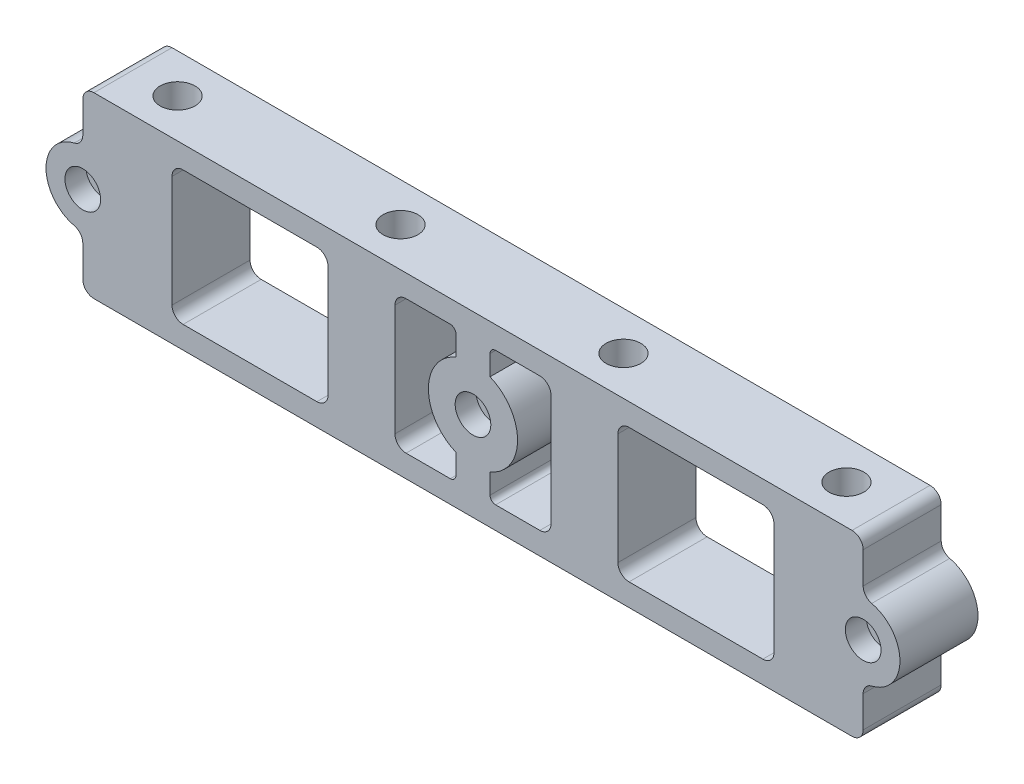
SolidWorks part; units mm, degrees
material "6061-T6 (SS)"
ref_plane "X-Y Datum" through (0, 0, 0) normal (0, 0, 1) x (1, 0, 0)
ref_plane "X-Z Datum" through (0, 0, 0) normal (0, 1, 0) x (1, 0, 0)
ref_plane "Y-Z Datum" through (0, 0, 0) normal (1, 0, 0) x (0, 0, -1)
other "Graphic1"
other "Graphic (Closed) -1"
other "Graphic2"
other "Graphic (Closed) -2"
other "Graphic3"
other "Graphic (Closed) -3"
sketch "Sketch1" plane through (0, 0, 0) normal (0, 0, 1) x (1, 0, 0)
  line L1 (8.7312, 20.32) -> (-186.5312, 20.32)
  line L5 (-8.7312, 0) -> (0, 0) construction
  line L7 (-186.5312, -20.32) -> (-186.5312, 20.32)
  line L8 (-8.7312, 0) -> (-16.6687, 0) construction
  line L9 (-8.7312, 0) -> (-8.7312, 20.32) construction
  line L10 (-8.7312, 20.32) -> (-16.6688, 20.32) construction
  line L11 (-16.6687, 0) -> (-16.6688, 20.32) construction
  line L12 (-67.4688, 0) -> (-59.5313, 0) construction
  line L13 (-67.4688, 0) -> (-67.4688, 20.32) construction
  line L14 (-67.4688, 20.32) -> (-59.5312, 20.32) construction
  line L15 (-59.5313, 0) -> (-59.5312, 20.32) construction
  line L17 (-186.5312, -20.32) -> (8.7312, -20.32)
  line L19 (8.7312, -20.32) -> (8.7312, 20.32)
  line L20 (-110.3313, 20.32) -> (-118.2687, 20.32) construction
  line L21 (-110.3313, 20.32) -> (-110.3313, 0) construction
  line L22 (-110.3313, 0) -> (-118.2687, 0) construction
  line L23 (-118.2687, 20.32) -> (-118.2687, 0) construction
  line L24 (-161.1312, 20.32) -> (-169.0687, 20.32) construction
  line L25 (-161.1312, 20.32) -> (-161.1313, 0) construction
  line L26 (-161.1313, 0) -> (-169.0688, 0) construction
  line L27 (-169.0687, 20.32) -> (-169.0688, 0) construction
  line L28 (0, 0) -> (8.7312, 0) construction
  line L29 (-177.8, 0) -> (-186.5312, 0) construction
  circle A0 centre (0, 0) radius 2.4892
  circle A4 centre (-177.8, 0) radius 2.4892
  circle A6 centre (-88.9, 0) radius 2.4892
  point P1 (-186.5312, 0)
  point P22 (-12.7, 0)
  point P23 (-63.5, 0)
  point P31 (-114.3, 0)
  point P32 (-165.1, 0)
  point P38 (-88.9, -20.32)
  dimension "D2" = 4.9784
  dimension "D3" = 12.7
  dimension "D1" = 50.8
  dimension "D4" = 12.7
  dimension "D6" = 7.9375
  dimension "D7" = 7.9375
  dimension "D8" = 40.64
  dimension "D11" = 50.8
  dimension "D12" = 50.8
extrude "Boss-Extrude1" add sketch "Sketch1" against normal blind 17.78
ref_plane "Plane1" through (0, 0, 0) normal (0, -1, 0) x (-1, 0, 0)
sketch "Sketch2" plane through (0, 20.32, 0) normal (0, 1, 0) x (1, 0, 0)
  line L0 (-186.5312, 0) -> (8.7313, 0) construction
  line L4 (0, 0) -> (0, 17.78) construction
  line L5 (8.7313, 17.78) -> (-186.5312, 17.78) construction
  circle A0 centre (-12.7, 8.89) radius 3.9688
  circle A2 centre (-63.5, 8.89) radius 3.9688
  circle A3 centre (-114.3, 8.89) radius 3.9687
  circle A4 centre (-165.1, 8.89) radius 3.9688
  dimension "D2" = 7.9375
  dimension "D1" = 4
  dimension "D3" = 8.89
  dimension "D4" = 12.7
  dimension "D5" = 50.8
extrude "Cut-Extrude1" cut sketch "Sketch2" against normal up to surface (40.64 mm away) up to face at (-88.9, -20.32, -8.89)
sketch "Sketch3" plane through (0, 0, 0) normal (0, 0, 1) x (1, 0, 0)
  circle A0 centre (0, 0) radius 4.064
  circle A1 centre (-88.9, 0) radius 4.064
  circle A2 centre (-177.8, 0) radius 4.064
  circle A3 centre (-177.8, 0) radius 2.4892 construction
  dimension "D1" = 8.128
extrude "Cut-Extrude2" cut sketch "Sketch3" against normal blind 4.7752
ref_point "Point1"
ref_point "Point2"
ref_point "Point3"
ref_point "Point4"
sketch "Sketch5" plane through (0, 0, 0) normal (0, 0, 1) x (1, 0, 0)
  line L0 (0, -20.32) -> (8.7312, -20.32)
  line L1 (0, -10.6225) -> (0, -20.32)
  line L2 (-186.5312, -20.32) -> (8.7312, -20.32) construction
  line L3 (0, 10.6225) -> (0, 20.32)
  line L4 (8.7312, 20.32) -> (-186.5312, 20.32) construction
  line L5 (8.7312, -20.32) -> (8.7312, 20.32)
  line L6 (8.7312, 20.32) -> (0, 20.32)
  line L7 (-88.9, -20.32) -> (-88.9, 20.32) construction
  line L8 (0, 0) -> (-20.32, 0) construction
  line L9 (-22.86, -15.24) -> (-53.34, -15.24)
  line L10 (-20.32, -12.7) -> (-20.32, 12.7)
  line L11 (-22.86, 15.24) -> (-53.34, 15.24)
  line L12 (-55.88, -12.7) -> (-55.88, 12.7)
  line L13 (-85.0119, -9.3866) -> (-85.0119, -13.97)
  line L14 (-83.7419, -15.24) -> (-73.66, -15.24)
  line L15 (-71.12, -12.7) -> (-71.12, 12.7)
  line L16 (-73.66, 15.24) -> (-83.7419, 15.24)
  line L17 (-85.0119, 13.97) -> (-85.0119, 9.3866)
  line L18 (-88.9, 0) -> (-85.0119, -9.3866) construction
  line L19 (-88.9, 0) -> (-85.0119, 9.3866) construction
  line L20 (-104.14, 15.24) -> (-94.0581, 15.24)
  line L21 (-106.68, -12.7) -> (-106.68, 12.7)
  line L22 (-94.0581, -15.24) -> (-104.14, -15.24)
  line L23 (-92.7881, -9.3866) -> (-92.7881, -13.97)
  line L24 (-92.7881, 13.97) -> (-92.7881, 9.3866)
  line L25 (-154.94, 15.24) -> (-124.46, 15.24)
  line L26 (-121.92, -12.7) -> (-121.92, 12.7)
  line L27 (-154.94, -15.24) -> (-124.46, -15.24)
  line L28 (-157.48, -12.7) -> (-157.48, 12.7)
  line L29 (-186.5312, -20.32) -> (-186.5312, 20.32)
  line L30 (-177.8, -20.32) -> (-186.5312, -20.32)
  line L31 (-177.8, -10.6225) -> (-177.8, -20.32)
  line L32 (-177.8, 10.6225) -> (-177.8, 20.32)
  line L33 (-186.5312, 20.32) -> (-177.8, 20.32)
  arc A0 (1.9493, 8.1522) -> (1.9493, -8.1522) centre (0, 0) cw
  arc A1 (-85.0119, -9.3866) -> (-85.0119, 9.3866) centre (-88.9, 0) ccw
  arc A2 (0, -10.6225) -> (1.9493, -8.1522) centre (2.54, -10.6225) cw
  arc A3 (-22.86, 15.24) -> (-20.32, 12.7) centre (-22.86, 12.7) cw
  arc A4 (-55.88, 12.7) -> (-53.34, 15.24) centre (-53.34, 12.7) cw
  arc A5 (-55.88, -12.7) -> (-53.34, -15.24) centre (-53.34, -12.7) ccw
  arc A6 (0, 10.6225) -> (1.9493, 8.1522) centre (2.54, 10.6225) ccw
  arc A7 (-22.86, -15.24) -> (-20.32, -12.7) centre (-22.86, -12.7) ccw
  arc A8 (-92.7881, -9.3866) -> (-92.7881, 9.3866) centre (-88.9, 0) cw
  arc A9 (-121.92, 12.7) -> (-124.46, 15.24) centre (-124.46, 12.7) ccw
  arc A10 (-121.92, -12.7) -> (-124.46, -15.24) centre (-124.46, -12.7) cw
  arc A11 (-154.94, 15.24) -> (-157.48, 12.7) centre (-154.94, 12.7) ccw
  arc A12 (-154.94, -15.24) -> (-157.48, -12.7) centre (-154.94, -12.7) cw
  arc A13 (-177.8, -10.6225) -> (-179.7493, -8.1522) centre (-180.34, -10.6225) ccw
  arc A14 (-179.7493, 8.1522) -> (-179.7493, -8.1522) centre (-177.8, 0) ccw
  arc A15 (-177.8, 10.6225) -> (-179.7493, 8.1522) centre (-180.34, 10.6225) cw
  arc A16 (-106.68, 12.7) -> (-104.14, 15.24) centre (-104.14, 12.7) cw
  arc A17 (-106.68, -12.7) -> (-104.14, -15.24) centre (-104.14, -12.7) ccw
  arc A18 (-73.66, 15.24) -> (-71.12, 12.7) centre (-73.66, 12.7) cw
  arc A19 (-73.66, -15.24) -> (-71.12, -12.7) centre (-73.66, -12.7) ccw
  arc A20 (-94.0581, 15.24) -> (-92.7881, 13.97) centre (-94.0581, 13.97) cw
  arc A21 (-83.7419, 15.24) -> (-85.0119, 13.97) centre (-83.7419, 13.97) ccw
  arc A22 (-94.0581, -15.24) -> (-92.7881, -13.97) centre (-94.0581, -13.97) ccw
  arc A23 (-85.0119, -13.97) -> (-83.7419, -15.24) centre (-83.7419, -13.97) ccw
  point P26 (0, -8.382)
  point P35 (-55.88, 15.24)
  point P38 (-55.88, -15.24)
  point P41 (0, 8.382)
  point P44 (-20.32, -15.24)
  point P76 (-106.68, 15.24)
  point P79 (-106.68, -15.24)
  point P82 (-71.12, 15.24)
  point P85 (-71.12, -15.24)
  point P86 (-38.1, -15.24)
  point P89 (-92.7881, 15.24)
  point P92 (-85.0119, 15.24)
  point P95 (-92.7881, -15.24)
  point P98 (-85.0119, -15.24)
  dimension "D1" = 8.382
  dimension "D5" = 10.16
  dimension "D7" = 2.54
  dimension "D8" = 2.54
  dimension "D10" = 2.54
  dimension "D12" = 1.27
  dimension "D2" = 46.8312
  dimension "D3" = 35.56
  dimension "D4" = 30.48
  dimension "D6" = 15.24
  dimension "D9" = 135
  dimension "D11" = 5.08
extrude "Cut-Extrude3" cut sketch "Sketch5" against normal up to surface (17.78 mm away) up to face at (-86.4108, 0, -17.78)
fillet "Fillet1" radius 2.54 4 edges at (0, -20.32, -8.89) (0, 20.32, -8.89) (-177.8, -20.32, -8.89) (-177.8, 20.32, -8.89)
